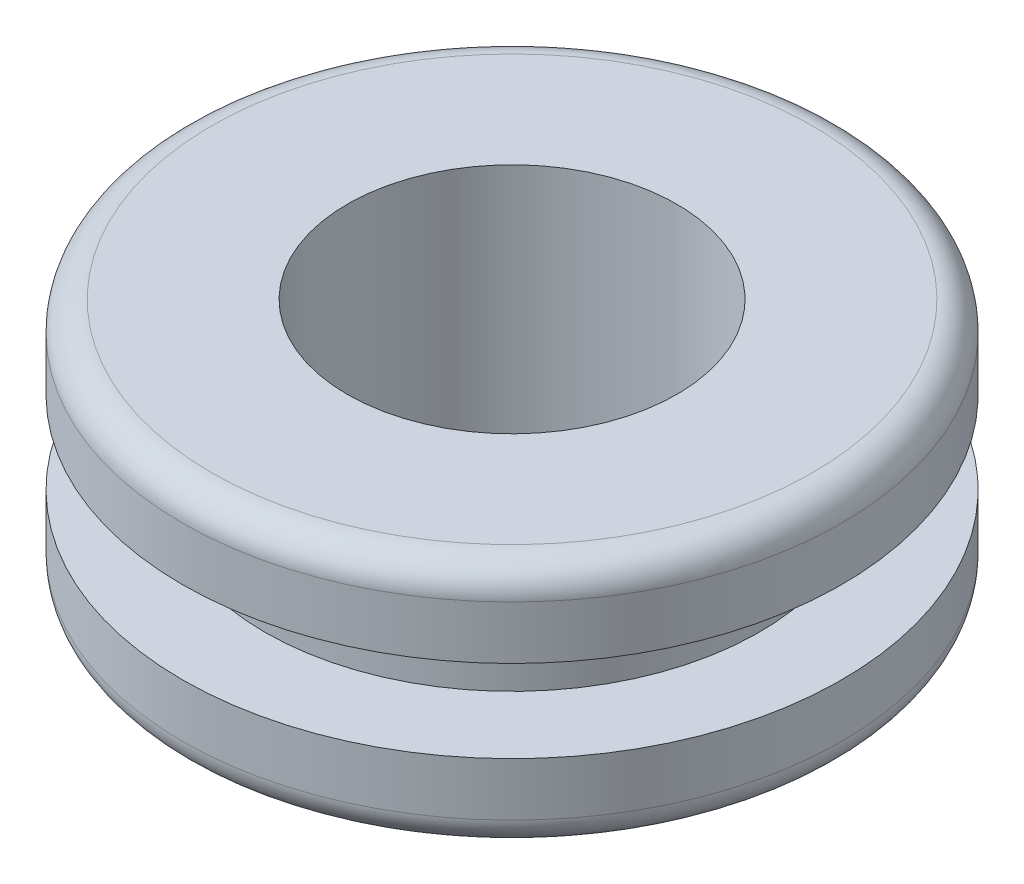
SolidWorks part; units mm, degrees
ref_plane "Front Plane" through (0, 0, 0) normal (0, 0, 1) x (1, 0, 0)
ref_plane "Top Plane" through (0, 0, 0) normal (0, 1, 0) x (1, 0, 0)
ref_plane "Right Plane" through (0, 0, 0) normal (1, 0, 0) x (0, 0, -1)
sketch "Sketch15" plane through (0, 0, 0) normal (0, 0, 1) x (1, 0, 0)
  line L0 (-3.175, -2.3812) -> (-3.175, 2.3812)
  line L1 (-3.175, 2.3812) -> (-5.7887, 2.3812)
  line L2 (-6.35, 1.82) -> (-6.35, 0.7938)
  line L3 (-6.35, 0.7938) -> (-4.7625, 0.7938)
  line L4 (-4.7625, 0.7938) -> (-4.7625, -0.7937)
  line L5 (-4.7625, -0.7937) -> (-6.35, -0.7937)
  line L6 (-6.35, -0.7937) -> (-6.35, -1.82)
  line L7 (-5.7887, -2.3812) -> (-3.175, -2.3812)
  line L8 (0, -2.3813) -> (0, 2.3812) construction
  line L10 (6.35, 0) -> (-6.35, 0) construction
  line L11 (3.175, 2.3812) -> (-3.175, 2.3812) construction
  line L12 (-5.7887, 2.3812) -> (-6.35, 1.82) construction
  arc A0 (-5.7887, 2.3812) -> (-6.35, 1.82) centre (-5.7887, 1.82) ccw
  arc A1 (-6.35, -1.82) -> (-5.7887, -2.3812) centre (-5.7887, -1.82) ccw
  point P14 (0, 0)
  point P17 (-182.5014, -4.2173)
  point P20 (0, 0)
  point P21 (0, 0)
  point P23 (0, 2.3812)
  dimension "D2" = 0.7937
  dimension "D3" = 0.7937
revolve "Revolve4" add sketch "Sketch15" angle 360 about L8
equation "\"D2@Sketch15\"=\"GRV@Sketch15\"/2"
